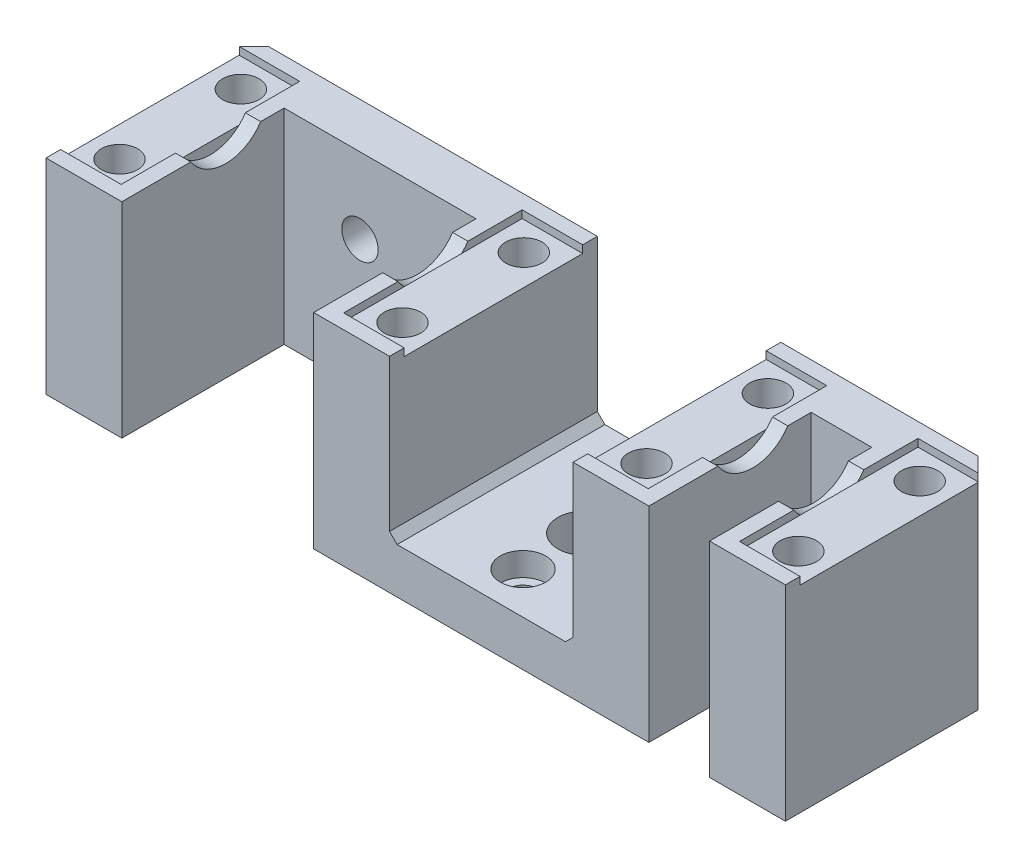
SolidWorks part; units mm, degrees
ref_plane "正面" through (0, 0, 0) normal (0, 0, 1) x (1, 0, 0)
ref_plane "平面" through (0, 0, 0) normal (0, 1, 0) x (1, 0, 0)
ref_plane "右側面" through (0, 0, 0) normal (1, 0, 0) x (0, 0, -1)
sketch "ｽｹｯﾁ2" plane through (0, 0, 0) normal (0, 1, 0) x (1, 0, 0)
  line L1 (-48.75, 13.7) -> (48.75, 13.7)
  line L2 (-48.75, 13.7) -> (-48.75, -13.7)
  line L3 (-48.75, -13.7) -> (48.75, -13.7)
  line L4 (48.75, 13.7) -> (48.75, -13.7)
  point P0 (0, 0)
  dimension "D1" = 97.5
  dimension "D2" = 13.7
  dimension "D3" = 13.7
extrude "ﾎﾞｽ - 押し出し1" add sketch "ｽｹｯﾁ2" along normal blind 6
sketch "ｽｹｯﾁ3" plane through (0, 6, 0) normal (0, 1, 0) x (1, 0, 0)
  line L0 (-48.75, -13.7) -> (48.75, -13.7) construction
  line L1 (-48.75, 13.7) -> (-38.75, 13.7)
  line L2 (-48.75, 13.7) -> (-48.75, -13.7)
  line L3 (-48.75, -13.7) -> (-38.75, -13.7)
  line L4 (-38.75, 13.7) -> (-38.75, -13.7)
  line L5 (48.75, 13.7) -> (-48.75, 13.7) construction
  line L6 (48.75, 13.7) -> (38.75, 13.7)
  line L7 (48.75, 13.7) -> (48.75, -13.7)
  line L8 (48.75, -13.7) -> (38.75, -13.7)
  line L9 (38.75, 13.7) -> (38.75, -13.7)
  line L10 (-13.45, 13.7) -> (-3.45, 13.7)
  line L11 (-13.45, 13.7) -> (-13.45, -13.7)
  line L12 (-13.45, -13.7) -> (-3.45, -13.7)
  line L13 (-3.45, 13.7) -> (-3.45, -13.7)
  line L14 (8.65, 13.7) -> (8.65, -13.7) construction
  line L15 (20.75, 13.7) -> (30.75, 13.7)
  line L16 (20.75, 13.7) -> (20.75, -13.7)
  line L17 (20.75, -13.7) -> (30.75, -13.7)
  line L18 (30.75, 13.7) -> (30.75, -13.7)
  dimension "D1" = 10
  dimension "D2" = 10
  dimension "D3" = 12.1
  dimension "D4" = 8
  dimension "D5" = 12.1
extrude "ﾎﾞｽ - 押し出し2" add sketch "ｽｹｯﾁ3" along normal blind 21
sketch "ｽｹｯﾁ5" plane through (0, 27, 0) normal (0, 1, 0) x (1, 0, 0)
  line L0 (0, 0) -> (-48.75, 0) construction
  line L1 (-48.75, 13.7) -> (-48.75, -13.7) construction
  line L2 (0, 0) -> (48.75, 0) construction
  line L3 (48.75, -13.7) -> (48.75, 13.7) construction
  line L4 (-3.45, -13.7) -> (-3.45, 13.7) construction
  line L9 (-48.75, 11.77) -> (-40.77, 11.77)
  line L10 (-48.75, 11.77) -> (-48.75, -11.77)
  line L11 (-48.75, -11.77) -> (-40.77, -11.77)
  line L12 (-40.77, 11.77) -> (-40.77, -11.77)
  line L13 (-48.75, 11.77) -> (-40.77, -11.77) construction
  line L14 (-48.75, -11.77) -> (-40.77, 11.77) construction
  line L15 (-11.43, 11.77) -> (-3.45, 11.77)
  line L16 (-11.43, 11.77) -> (-11.43, -11.77)
  line L17 (-11.43, -11.77) -> (-3.45, -11.77)
  line L18 (-3.45, 11.77) -> (-3.45, -11.77)
  line L19 (-11.43, 11.77) -> (-3.45, -11.77) construction
  line L20 (-11.43, -11.77) -> (-3.45, 11.77) construction
  line L21 (20.75, 13.7) -> (20.75, -13.7) construction
  line L22 (28.73, 11.77) -> (20.75, 11.77)
  line L23 (28.73, 11.77) -> (28.73, -11.77)
  line L24 (28.73, -11.77) -> (20.75, -11.77)
  line L25 (20.75, 11.77) -> (20.75, -11.77)
  line L26 (28.73, 11.77) -> (20.75, -11.77) construction
  line L27 (28.73, -11.77) -> (20.75, 11.77) construction
  line L28 (40.77, 11.77) -> (48.75, 11.77)
  line L29 (40.77, 11.77) -> (40.77, -11.77)
  line L30 (40.77, -11.77) -> (48.75, -11.77)
  line L31 (48.75, 11.77) -> (48.75, -11.77)
  line L32 (40.77, 11.77) -> (48.75, -11.77) construction
  line L33 (40.77, -11.77) -> (48.75, 11.77) construction
  point P5 (-44.76, 0)
  point P13 (-7.44, 0)
  point P20 (24.74, 0)
  point P25 (44.76, 0)
  dimension "D1" = 23.54
  dimension "D2" = 7.98
extrude "ｶｯﾄ - 押し出し1" cut sketch "ｽｹｯﾁ5" against normal blind 1
sketch "ｽｹｯﾁ7" plane through (0, 26, 0) normal (0, 1, 0) x (1, 0, 0)
  line L0 (-48.75, 0) -> (48.75, 0) construction
  line L1 (-48.75, 11.77) -> (-48.75, -11.77) construction
  line L2 (48.75, -11.77) -> (48.75, 11.77) construction
  line L3 (-44.76, 11.77) -> (-44.76, -11.77) construction
  line L4 (-40.77, 11.77) -> (-48.75, 11.77) construction
  line L5 (-48.75, -11.77) -> (-40.77, -11.77) construction
  line L6 (-7.44, 11.77) -> (-7.44, -11.77) construction
  line L7 (-3.45, 11.77) -> (-11.43, 11.77) construction
  line L8 (-11.43, -11.77) -> (-3.45, -11.77) construction
  line L9 (24.74, 11.77) -> (24.74, -11.77) construction
  line L10 (28.73, 11.77) -> (20.75, 11.77) construction
  line L11 (20.75, -11.77) -> (28.73, -11.77) construction
  line L12 (44.76, 11.77) -> (44.76, -11.77) construction
  line L13 (48.75, 11.77) -> (40.77, 11.77) construction
  line L14 (40.77, -11.77) -> (48.75, -11.77) construction
  circle A0 centre (-44.76, 8) radius 1.7
  circle A1 centre (-44.76, -8) radius 1.7
  circle A2 centre (-7.44, 8) radius 1.7
  circle A3 centre (-7.44, -8) radius 1.7
  circle A4 centre (24.74, 8) radius 1.7
  circle A5 centre (24.74, -8) radius 1.7
  circle A6 centre (44.76, 8) radius 1.7
  circle A7 centre (44.76, -8) radius 1.7
  dimension "D3" = 3.4
  dimension "D1" = 8
  dimension "D2" = 8
extrude "ｶｯﾄ - 押し出し2" cut sketch "ｽｹｯﾁ7" against normal through all
sketch "ｽｹｯﾁ8" plane through (0, 6, 0) normal (0, 1, 0) x (1, 0, 0)
  line L0 (20.75, 0) -> (-3.45, 0) construction
  line L1 (20.75, 13.7) -> (20.75, -13.7) construction
  line L2 (-3.45, -13.7) -> (-3.45, 13.7) construction
  line L3 (8.65, 0) -> (8.65, -13.7) construction
  line L4 (-3.45, -13.7) -> (20.75, -13.7) construction
  line L5 (8.65, -13.7) -> (8.65, 13.7) construction
  line L6 (20.75, 13.7) -> (-3.45, 13.7) construction
  circle A0 centre (8.65, 0) radius 3.6
  circle A1 centre (8.65, 8.2) radius 1.8
  circle A2 centre (8.65, -8.2) radius 1.8
  dimension "D1" = 7.2
  dimension "D2" = 3.6
  dimension "D3" = 8.2
  dimension "D4" = 8.2
extrude "ｶｯﾄ - 押し出し3" cut sketch "ｽｹｯﾁ8" against normal through all
chamfer "面取り1" distance 2 angle 45 2 edges at (48.75, 13.5, -13.7) (-48.75, 13.5, -13.7)
sketch "ｽｹｯﾁ13" plane through (0, 6, 0) normal (0, 1, 0) x (1, 0, 0)
  line L0 (38.75, 13.7) -> (38.75, -13.7) construction
  line L1 (30.75, 13.7) -> (38.75, 13.7)
  line L2 (30.75, 13.7) -> (30.75, 7.7)
  line L3 (30.75, 7.7) -> (38.75, 7.7)
  line L4 (38.75, 13.7) -> (38.75, 7.7)
  line L5 (-13.45, 13.7) -> (-13.45, -13.7) construction
  line L6 (-38.75, 13.7) -> (-13.45, 13.7)
  line L7 (-38.75, 13.7) -> (-38.75, 7.7)
  line L8 (-38.75, 7.7) -> (-13.45, 7.7)
  line L9 (-13.45, 13.7) -> (-13.45, 7.7)
  dimension "D1" = 6
  dimension "D2" = 6
extrude "ﾎﾞｽ - 押し出し3" add sketch "ｽｹｯﾁ13" along normal up to surface (21 mm away) up to face at (25.245, 27, 0)
sketch "ｽｹｯﾁ14" plane through (0, 0, -7.7) normal (0, 0, 1) x (1, 0, 0)
  line L2 (-35.2316, 17) -> (43.2436, 17) construction
  line L3 (-13.45, 27) -> (-3.45, 27) construction
  line L4 (-48.75, 27) -> (-48.75, 0) construction
  line L5 (48.75, 27) -> (48.75, 0) construction
  circle A0 centre (-28.75, 17) radius 2.4
  circle A2 centre (34.75, 17) radius 2.4
  dimension "D2" = 4.8
  dimension "D1" = 10
  dimension "D3" = 20
  dimension "D4" = 14
extrude "ｶｯﾄ - 押し出し9" cut sketch "ｽｹｯﾁ14" against normal blind 10
sketch "ｽｹｯﾁ15" plane through (0, 6, 0) normal (0, 1, 0) x (1, 0, 0)
  line L0 (-13.45, 7.7) -> (-13.45, -13.7) construction
  line L1 (-38.75, 7.7) -> (-13.45, 7.7)
  line L2 (-38.75, 7.7) -> (-38.75, -13.7)
  line L3 (-38.75, -13.7) -> (-13.45, -13.7)
  line L4 (-13.45, 7.7) -> (-13.45, -13.7)
  line L5 (-13.45, 7.7) -> (-13.45, -13.7) construction
  line L7 (30.75, 7.7) -> (38.75, 7.7)
  line L8 (30.75, 7.7) -> (30.75, -13.7)
  line L9 (30.75, -13.7) -> (38.75, -13.7)
  line L10 (38.75, 7.7) -> (38.75, -13.7)
extrude "ｶｯﾄ - 押し出し10" cut sketch "ｽｹｯﾁ15" against normal blind 10
sketch "ｽｹｯﾁ16" plane through (0, 6, 0) normal (0, 1, 0) x (1, 0, 0)
  circle A0 centre (8.65, 8.2) radius 3
  circle A1 centre (8.65, -8.2) radius 3
  dimension "D1" = 6
extrude "ｶｯﾄ - 押し出し11" cut sketch "ｽｹｯﾁ16" against normal blind 3.1
sketch "ｽｹｯﾁ17" plane through (0, 26, 0) normal (0, 1, 0) x (1, 0, 0)
  circle A0 centre (-44.76, 8) radius 2.4
  circle A1 centre (-44.76, -8) radius 2.4
  circle A2 centre (-7.44, 8) radius 2.4
  circle A3 centre (-7.44, -8) radius 2.4
  circle A4 centre (24.74, 8) radius 2.4
  circle A5 centre (24.74, -8) radius 2.4
  circle A6 centre (44.76, 8) radius 2.4
  circle A7 centre (44.76, -8) radius 2.4
  dimension "D1" = 4.8
extrude "ｶｯﾄ - 押し出し12" cut sketch "ｽｹｯﾁ17" against normal blind 4.1
sketch "ｽｹｯﾁ18" plane through (38.75, 0, 0) normal (-1, 0, 0) x (0, 0, 1)
  line L0 (0, 0) -> (0, 27.8751) construction
  line L1 (-11.7, 26) -> (11.77, 26) construction
  circle A0 centre (0, 30) radius 5.5
  dimension "D1" = 11
  dimension "D2" = 4
extrude "ｶｯﾄ - 押し出し13" cut sketch "ｽｹｯﾁ18" against normal up to vertex (2.02 mm away) and the other way up to vertex (10.02 mm away)
sketch "ｽｹｯﾁ20" plane through (-38.75, 0, 0) normal (1, 0, 0) x (0, 0, -1)
  line L0 (-3.7749, 26) -> (-11.77, 26) construction
  circle A0 centre (0, 30) radius 5.5
  dimension "D1" = 11
  dimension "D2" = 4
extrude "ｶｯﾄ - 押し出し15" cut sketch "ｽｹｯﾁ20" against normal up to vertex (2.02 mm away) and the other way up to vertex (27.32 mm away)
chamfer "面取り2" distance 1 angle 45 2 edges at (20.75, 6, 0) (-3.45, 6, 0)
sketch "ｽｹｯﾁ21" plane through (0, 21.9, 0) normal (0, 1, 0) x (1, 0, 0)
  circle A0 centre (-7.44, 8) radius 1.7
  circle A1 centre (-44.76, 8) radius 1.7
  circle A2 centre (24.74, 8) radius 1.5497
  circle A3 centre (-44.76, -8) radius 1.7
  circle A4 centre (-7.44, -8) radius 1.7
  circle A5 centre (24.74, -8) radius 1.7
  circle A6 centre (44.76, 8) radius 1.7
  circle A7 centre (44.76, -8) radius 1.7
extrude "ﾎﾞｽ - 押し出し4" add sketch "ｽｹｯﾁ21" against normal up to surface (21.9 mm away) up to face at (8.65, 0, 10)
sketch "ｽｹｯﾁ19" plane through (-38.75, 0, 0) normal (1, 0, 0) x (0, 0, -1)
